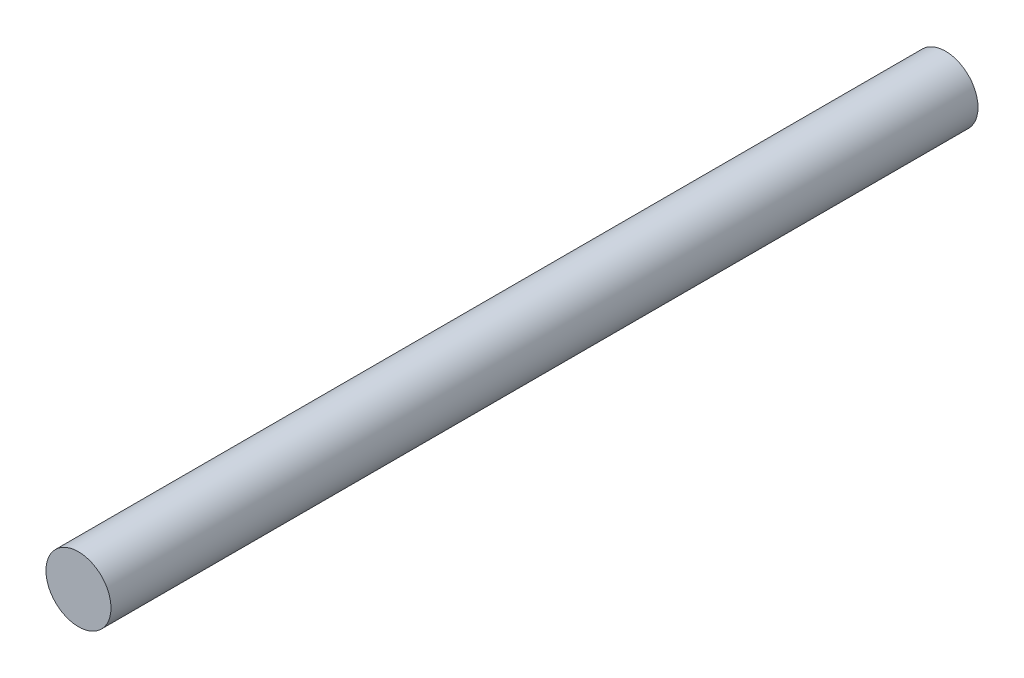
SolidWorks part; units mm, degrees
ref_plane "Front Plane" through (0, 0, 0) normal (0, 0, 1) x (1, 0, 0)
ref_plane "Top Plane" through (0, 0, 0) normal (0, 1, 0) x (1, 0, 0)
ref_plane "Right Plane" through (0, 0, 0) normal (1, 0, 0) x (0, 0, -1)
sketch "Esquisse1" plane through (0, 0, 0) normal (0, 0, 1) x (1, 0, 0)
  circle A0 centre (0, 0) radius 3
  dimension "D1" = 6
extrude "Boss.-Extru.1" add sketch "Esquisse1" along normal blind 80
